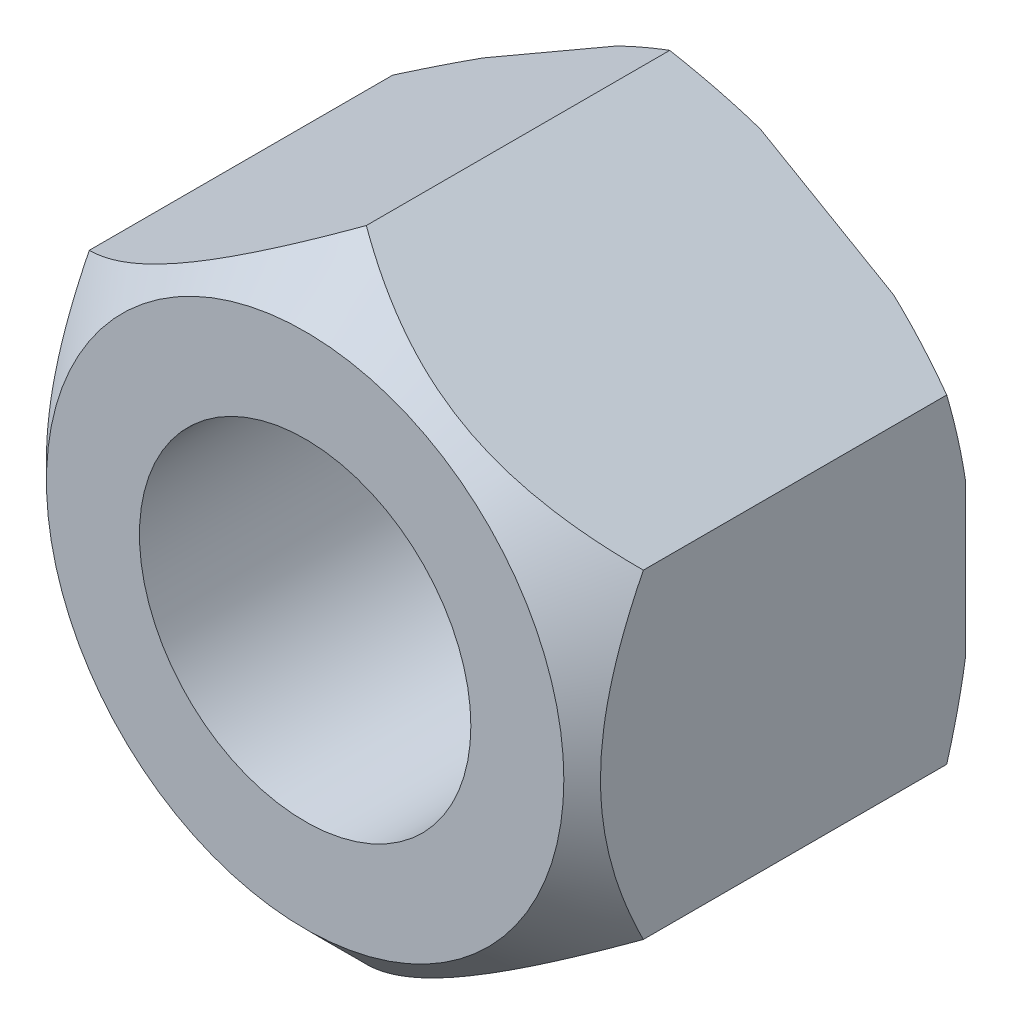
SolidWorks part; units mm, degrees
ref_plane "基准面1" through (0, 0, 0) normal (0, 0, 1) x (1, 0, 0)
ref_plane "基准面2" through (0, 0, 0) normal (0, 1, 0) x (1, 0, 0)
ref_plane "基准面3" through (0, 0, 0) normal (1, 0, 0) x (0, 0, -1)
sketch "尺寸草图" plane through (0, 0, 0) normal (0, 0, 1) x (1, 0, 0)
  line L0 (0, 0) -> (29.63, 0)
  line L1 (0, 0) -> (13, 0)
  line L2 (13, 0) -> (29.63, 0)
  line L3 (-11.4286, 0) -> (0, 0)
  point P3 (12, 0)
  point P4 (1.5, 0)
  point P5 (20.03, 0)
  point P7 (8.3, 0)
  point P8 (18, 0)
  point P15 (25, 0)
  dimension "D1" = 11.4286
  dimension "D" = 12
  dimension "P" = 1.5
  dimension "e(min)" = 20.03
  dimension "mw(min)" = 8.3
  dimension "s(max)" = 18
  dimension "da(max)" = 13
  dimension "dw(min)" = 16.63
  dimension "h(max)" = 12
sketch "草图1" plane through (0, 0, 0) normal (0, 0, 1) x (1, 0, 0)
  line L0 (-8.6732, 0) -> (8.6732, 0) construction
  line L1 (0, 10.015) -> (0, -10.015) construction
  line L3 (0, 10.015) -> (-8.6732, 5.0075)
  line L4 (-8.6732, 5.0075) -> (-8.6732, -5.0075)
  line L5 (-8.6732, -5.0075) -> (0, -10.015)
  line L6 (0, -10.015) -> (8.6732, -5.0075)
  line L7 (8.6732, -5.0075) -> (8.6732, 5.0075)
  line L8 (8.6732, 5.0075) -> (0, 10.015)
  circle A0 centre (0, 0) radius 8.6732 construction
  circle A1 centre (0, 0) radius 5.1881
  dimension "D" = 10.3763
  dimension "e" = 20.03
extrude "基体-拉伸" add sketch "草图1" along normal blind 12
cosmetic thread "装饰螺纹线1" parameters "D2"=12
sketch "草图2" plane through (0, 0, 0) normal (0, 0, -1) x (-1, 0, 0)
  circle A0 centre (0, 0) radius 9
  circle A1 centre (0, 0) radius 5.1881 construction
  dimension "s" = 18
extrude "切除-拉伸1" cut sketch "草图2" against normal through all draft 60 flip side to cut
chamfer "倒角1" distance 0.1964 angle 45 1 edges at (5.1881, 0, 0)
sketch "草图9" plane through (0, 0, 12) normal (0, 0, 1) x (1, 0, 0)
  circle A0 centre (0, 0) radius 8.1
  dimension "s*0.9" = 16.2
extrude "切除-拉伸7" cut sketch "草图9" against normal through all draft 45 flip side to cut
